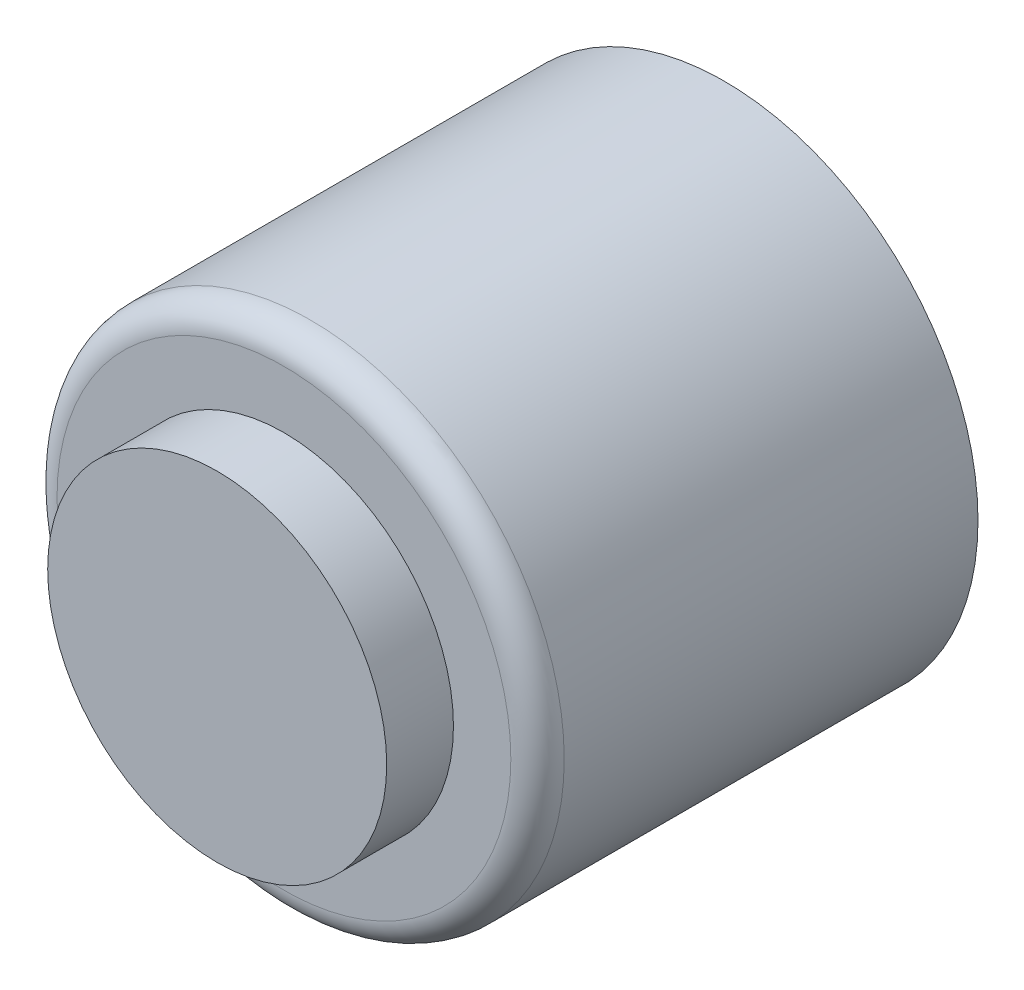
SolidWorks part; units mm, degrees
material "Acrylic (Medium-high impact)"
ref_plane "Front Plane" through (0, 0, 0) normal (0, 0, 1) x (1, 0, 0)
ref_plane "Top Plane" through (0, 0, 0) normal (0, 1, 0) x (1, 0, 0)
ref_plane "Right Plane" through (0, 0, 0) normal (1, 0, 0) x (0, 0, -1)
sketch "Sketch1" plane through (0, 0, 0) normal (1, 0, 0) x (0, 0, -1)
  line L0 (0, 0) -> (0, -12.7)
  line L1 (0, -12.7) -> (5, -12.7)
  line L2 (5, -12.7) -> (5, -19)
  line L3 (5, -19) -> (38, -19)
  line L4 (38, -19) -> (38, -18)
  line L5 (38, -18) -> (34.5174, -14.5174)
  line L6 (0, 0) -> (6, 0)
  line L7 (6, 0) -> (38, 0)
  arc A0 (34.5174, -14.5174) -> (38, 0) centre (6, 0) ccw
  point P10 (32.7661, -19)
  point P11 (31.0315, -16.9094)
  point P12 (35.3842, -19)
  point P13 (0, 0)
  dimension "D7" = 32
  dimension "D1" = 12.7
  dimension "D2" = 135
  dimension "D3" = 19
  dimension "D4" = 5
  dimension "D5" = 1
  dimension "D6" = 38
revolve "Revolve1" add sketch "Sketch1" angle 360 about L6
fillet "Fillet1" radius 2 1 edges at (19, 0, -5)
